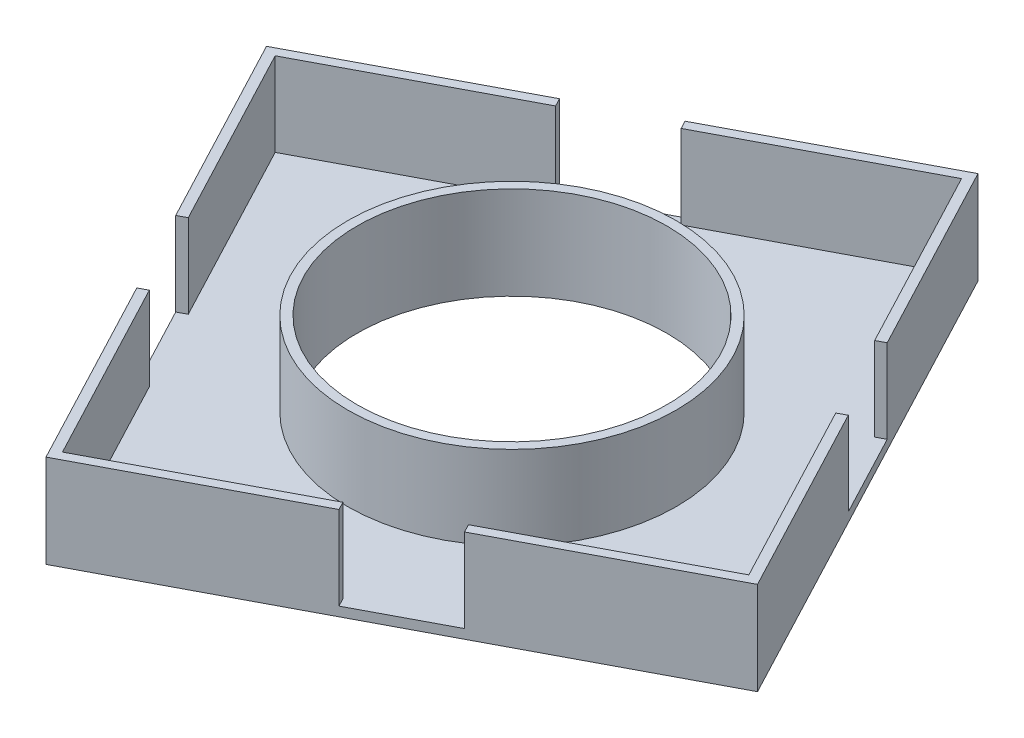
SolidWorks part; units mm, degrees
ref_plane "Front Plane" through (0, 0, 0) normal (0, 0, 1) x (1, 0, 0)
ref_plane "Top Plane" through (0, 0, 0) normal (0, 1, 0) x (1, 0, 0)
ref_plane "Right Plane" through (0, 0, 0) normal (1, 0, 0) x (0, 0, -1)
sketch "Sketch2" plane through (0, 0, 0) normal (0, 1, 0) x (1, 0, 0)
  line L1 (-35.583, -114.8209) -> (114.8209, -35.583)
  line L2 (114.8209, -35.583) -> (35.583, 114.8209)
  line L3 (35.583, 114.8209) -> (-114.8209, 35.583)
  line L4 (-114.8209, 35.583) -> (-35.583, -114.8209)
  circle A0 centre (0, 0) radius 50
  circle A1 centre (0, 0) radius 85 construction
extrude "Boss-Extrude1" add sketch "Sketch2" along normal blind 30 contours L3 L4 L1 L2 | A0
shell "Shell1" thickness 3
sketch "Sketch7" plane through (0, 30, 0) normal (0, 1, 0) x (1, 0, 0)
  line L1 (79.5394, 24.9497) -> (82.1936, 26.348)
  line L2 (110.7684, -34.3271) -> (34.3271, 110.7684) construction
  line L3 (114.8209, -35.583) -> (35.583, 114.8209) construction
  line L4 (82.1936, 26.348) -> (68.2104, 52.8899)
  line L5 (68.2104, 52.8899) -> (65.5562, 51.4916)
  line L6 (65.5562, 51.4916) -> (79.5394, 24.9497)
  line L7 (51.4916, -65.5562) -> (24.9497, -79.5394)
  line L8 (24.9497, -79.5394) -> (26.348, -82.1936)
  line L9 (26.348, -82.1936) -> (52.8899, -68.2104)
  line L10 (52.8899, -68.2104) -> (51.4916, -65.5562)
  line L11 (-65.5562, -51.4916) -> (-79.5394, -24.9497)
  line L12 (-79.5394, -24.9497) -> (-82.1936, -26.348)
  line L13 (-82.1936, -26.348) -> (-68.2104, -52.8899)
  line L14 (-68.2104, -52.8899) -> (-65.5562, -51.4916)
  line L15 (-51.4916, 65.5562) -> (-24.9497, 79.5394)
  line L16 (-24.9497, 79.5394) -> (-26.348, 82.1936)
  line L17 (-26.348, 82.1936) -> (-52.8899, 68.2104)
  line L18 (-52.8899, 68.2104) -> (-51.4916, 65.5562)
  point P9 (75.202, 39.619)
  point P10 (75.202, 39.619)
  point P25 (0, 0)
  dimension "D1" = 30
  dimension "D2" = 15
  dimension "D3" = 4
extrude "Cut-Extrude3" cut sketch "Sketch7" against normal blind 27
